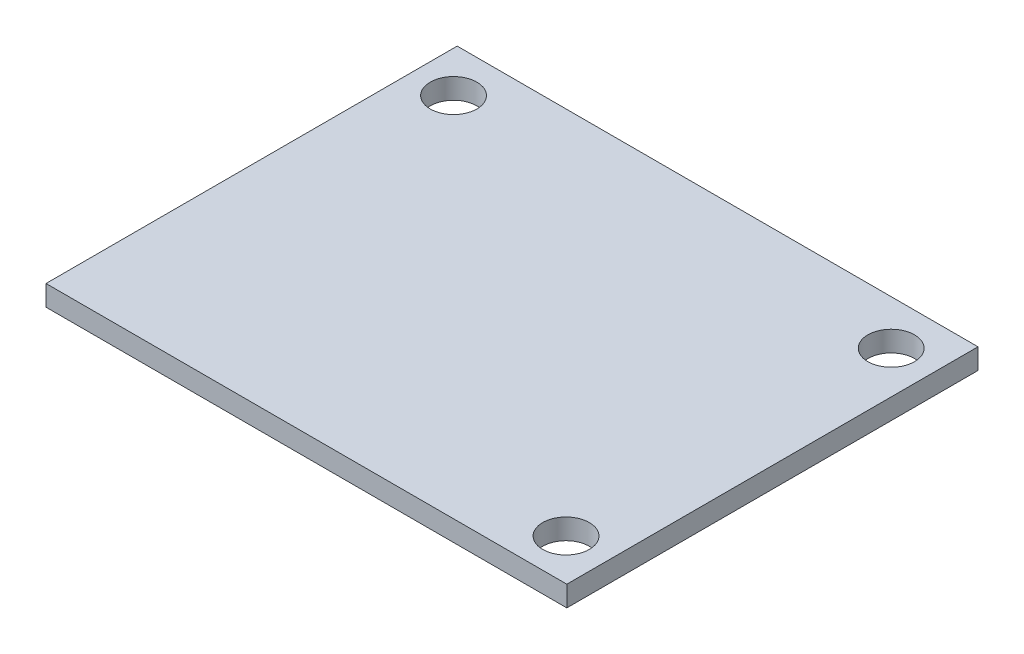
SolidWorks part; units mm, degrees
ref_plane "Front Plane" through (0, 0, 0) normal (0, 0, 1) x (1, 0, 0)
ref_plane "Top Plane" through (0, 0, 0) normal (0, 1, 0) x (1, 0, 0)
ref_plane "Right Plane" through (0, 0, 0) normal (1, 0, 0) x (0, 0, -1)
sketch "Sketch1" plane through (0, 0, 0) normal (0, 1, 0) x (1, 0, 0)
  line L1 (-19, 15) -> (19, 15)
  line L2 (-19, 15) -> (-19, -15)
  line L3 (-19, -15) -> (19, -15)
  line L4 (19, 15) -> (19, -15)
  line L5 (-19, 15) -> (19, -15) construction
  line L6 (-19, -15) -> (19, 15) construction
  point P0 (0, 0)
extrude "Boss-Extrude1" add sketch "Sketch1" along normal blind 1.5
sketch "Sketch2" plane through (0, 1.5, 0) normal (0, 1, 0) x (1, 0, 0)
  circle A0 centre (-16.0063, 11.742) radius 1.7
  circle A1 centre (15.9255, 11.742) radius 1.7
  circle A2 centre (15.9255, -11.9845) radius 1.7
extrude "Cut-Extrude1" cut sketch "Sketch2" against normal through all
